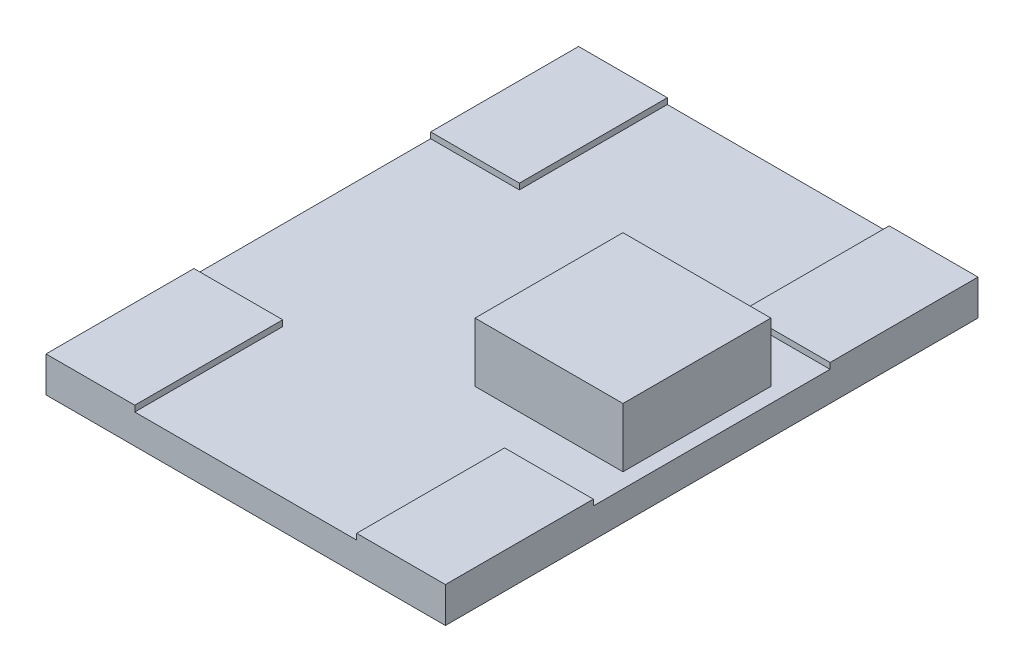
SolidWorks part; units mm, degrees
ref_plane "Спереди" through (0, 0, 0) normal (0, 0, 1) x (1, 0, 0)
ref_plane "Сверху" through (0, 0, 0) normal (0, 1, 0) x (1, 0, 0)
ref_plane "Справа" through (0, 0, 0) normal (1, 0, 0) x (0, 0, -1)
sketch "Эскиз1" plane through (0, 0, 0) normal (0, 1, 0) x (1, 0, 0)
  line L1 (-6.75, -9) -> (6.75, -9)
  line L2 (-6.75, -9) -> (-6.75, 9)
  line L3 (-6.75, 9) -> (6.75, 9)
  line L4 (6.75, -9) -> (6.75, 9)
  line L5 (-6.75, -9) -> (6.75, 9) construction
  line L6 (-6.75, 9) -> (6.75, -9) construction
  point P0 (0, 0)
  dimension "D1" = 13.5
  dimension "D2" = 18
extrude "Бобышка-Вытянуть1" add sketch "Эскиз1" along normal blind 1
sketch "Эскиз2" plane through (0, 1, 0) normal (0, 1, 0) x (1, 0, 0)
  line L0 (-6.75, -9) -> (-6.75, -4)
  line L1 (-6.75, -9) -> (-3.75, -9)
  line L2 (-6.75, -4) -> (-3.75, -4)
  line L3 (-3.75, -9) -> (-3.75, -4)
  line L4 (-6.75, 9) -> (-6.75, -9) construction
  line L5 (0, -50) -> (0, 50) construction
  line L6 (6.75, -4) -> (3.75, -4)
  line L7 (3.75, -9) -> (3.75, -4)
  line L8 (6.75, -9) -> (3.75, -9)
  line L9 (6.75, -9) -> (6.75, -4)
  line L10 (-50, 0) -> (50, 0) construction
  line L11 (-6.75, 4) -> (-3.75, 4)
  line L12 (-3.75, 9) -> (-3.75, 4)
  line L13 (-6.75, 9) -> (-3.75, 9)
  line L14 (-6.75, 9) -> (-6.75, 4)
  line L15 (6.75, 9) -> (6.75, 4)
  line L16 (6.75, 9) -> (3.75, 9)
  line L17 (3.75, 9) -> (3.75, 4)
  line L18 (6.75, 4) -> (3.75, 4)
  dimension "D1" = 3
  dimension "D2" = 5
extrude "Бобышка-Вытянуть2" add sketch "Эскиз2" along normal blind 0.2
sketch "Эскиз3" plane through (0, 1, 0) normal (0, 1, 0) x (1, 0, 0)
  line L0 (3.75, 4) -> (3.75, -4) construction
  line L1 (6.25, -2.5) -> (1.25, -2.5)
  line L2 (6.25, -2.5) -> (6.25, 2.5)
  line L3 (6.25, 2.5) -> (1.25, 2.5)
  line L4 (1.25, -2.5) -> (1.25, 2.5)
  line L5 (6.25, -2.5) -> (1.25, 2.5) construction
  line L6 (6.25, 2.5) -> (1.25, -2.5) construction
  point P0 (3.75, 0)
  dimension "D1" = 5
extrude "Бобышка-Вытянуть3" add sketch "Эскиз3" along normal blind 2
